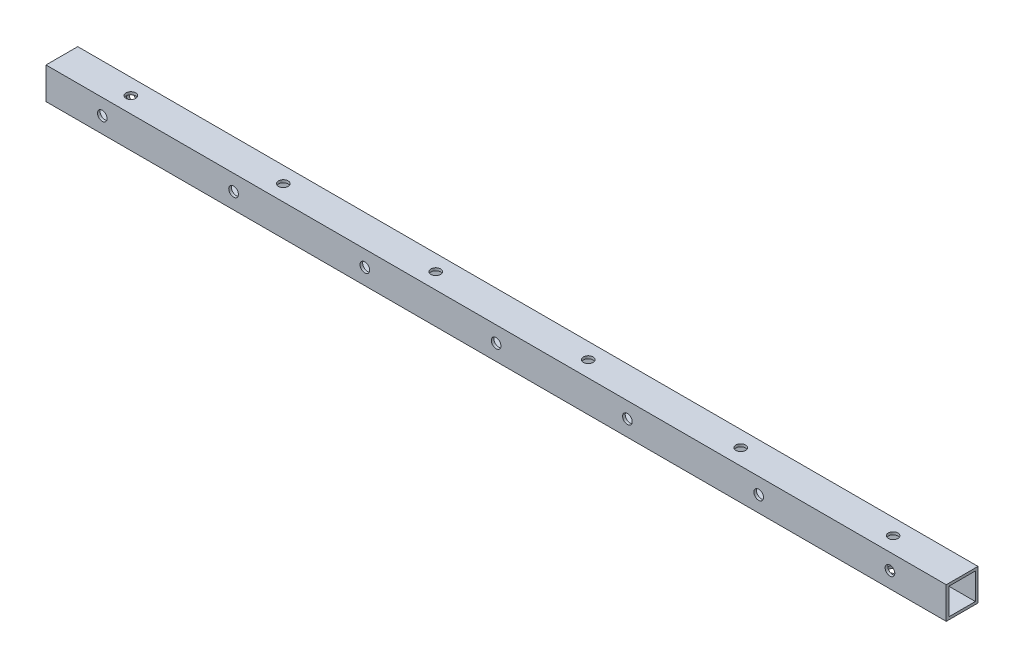
SolidWorks part; units mm, degrees
material "1060 Alloy"
ref_plane "Front Plane" through (0, 0, 0) normal (0, 0, 1) x (1, 0, 0)
ref_plane "Top Plane" through (0, 0, 0) normal (0, 1, 0) x (1, 0, 0)
ref_plane "Right Plane" through (0, 0, 0) normal (1, 0, 0) x (0, 0, -1)
sketch "Sketch1" plane through (0, 0, 0) normal (1, 0, 0) x (0, -1, 0)
  line L1 (-9.525, 9.525) -> (9.525, 9.525)
  line L2 (-9.525, 9.525) -> (-9.525, -9.525)
  line L3 (-9.525, -9.525) -> (9.525, -9.525)
  line L4 (9.525, 9.525) -> (9.525, -9.525)
  line L5 (-9.525, 9.525) -> (9.525, -9.525) construction
  line L6 (-9.525, -9.525) -> (9.525, 9.525) construction
  line L7 (-7.9375, 7.9375) -> (7.9375, 7.9375)
  line L8 (-7.9375, 7.9375) -> (-7.9375, -7.9375)
  line L9 (-7.9375, -7.9375) -> (7.9375, -7.9375)
  line L10 (7.9375, 7.9375) -> (7.9375, -7.9375)
  line L11 (-7.9375, 7.9375) -> (7.9375, -7.9375) construction
  line L12 (-7.9375, -7.9375) -> (7.9375, 7.9375) construction
  point P0 (0, 0)
  point P5 (0, 0)
  dimension "D2" = 19.05
  dimension "D1" = 15.875
extrude "Tube" add sketch "Sketch1" along normal blind 539.9532
sketch "Sketch2" plane through (0, 0, 9.525) normal (0, 0, 1) x (1, 0, 0)
  line L0 (506.1966, 0) -> (539.9532, 0) construction
  line L1 (539.9532, 9.525) -> (539.9532, -9.525) construction
  line L2 (539.9532, 0) -> (559.0032, 0) construction
  line L4 (559.0032, 0) -> (562.0766, 0) construction
  circle A2 centre (506.1966, 0) radius 2.8956
  dimension "D1" = 5.7912
  dimension "D2" = 19.05
  dimension "D3" = 3.0734
  dimension "D4" = 55.88
extrude "RearWallHoles" cut sketch "Sketch2" against normal through all
pattern_linear "LPattern1" count 7 spacing 78.74 along (-1, 0, 0) of "RearWallHoles"
sketch "Sketch3" plane through (0, 9.525, 0) normal (0, 1, 0) x (1, 0, 0)
  line L0 (0, 0) -> (-19.05, 0) construction
  line L1 (-19.05, 0) -> (-22.1234, 0) construction
  line L2 (0, 0) -> (41.3766, 0) construction
  circle A0 centre (41.3766, 0) radius 2.8956
  dimension "D1" = 5.7912
  dimension "D2" = 3.0734
  dimension "D3" = 19.05
  dimension "D4" = 63.5
extrude "RearTopHoleMaster" cut sketch "Sketch3" against normal through all
pattern_linear "LPattern2" count 6 spacing 91.44 along (1, 0, 0) of "RearTopHoleMaster"
equation "\"Height\"= 32in"
equation "\"Width\"= 23in"
equation "\"Depth\"= 20in"
equation "\"Plexi\"= .121in"
equation "\"Cutwidth\"= .016in"
equation "\"Earsize\"= 1in + \"Cutwidth\" /2"
equation "\"Slotsize\" = 1in - \"CutWidth\" / 2"
equation "\"InnerHeight\" = \"Height\" -2 * \"Plexi\""
equation "\"InnerWidth\" = \"Width\" - 2* \"Plexi\""
equation "\"RearHoleSpacing\" = (\"Width\" - 2*\"RearHolesBorder\") / (\"RearNumHoles\"-1)"
equation "\"D4@Sketch2\"=\"RearHolesBorder\""
equation "\"Boxsize\" = .75in"
equation "\"Boxinner\" = .625in"
equation "\"InnerDepth\" = \"Depth\" - 2*\"Plexi\""
equation "\"RearNumHoles\" = 7"
equation "\"RearHolesBorder\" = 2.2"
equation "\"SideVertNumHoles\" = 6"
equation "\"SideVertHolesBorder\" = \"CornerCube\"+\"FingerLength\"+.9"
equation "\"RivetDia\" = .228in"
equation "\"SlotDepth\" = \"Plexi\" + 0.75in + .005in"
equation "\"SideSlotWidth\"   = \"Plexi\"+.005in"
equation "\"SidePanelVertSpacing\" = (\"Height\"-2*(1.75-\"Plexi\")) / 5"
equation "\"BottomPanelSideHoleSpacing\" = (\"InnerDepth\"-2*(1.75-\"Plexi\")) / 4"
equation "\"D2@Sketch1\"=\"Boxsize\""
equation "\"D1@Sketch1\"=\"Boxinner\""
equation "\"CornerCube\" = 0.75in"
equation "\"RearBarLength\" = (\"InnerWidth\"-2*\"CornerCube\")"
equation "\"D1@Sketch2\"=\"RivetDia\""
equation "\"D2@Sketch2\"=\"CornerCube\""
equation "\"D3@Sketch2\"=\"Plexi\""
equation "\"D3@LPattern1\"=\"RearHoleSpacing\""
equation "\"D1@LPattern1\"=\"RearNumHoles\""
equation "\"D1@Tube\"=\"RearBarLength\""
equation "\"D1@Sketch3\"=\"RivetDia\""
equation "\"D2@Sketch3\"=\"Plexi\""
equation "\"D3@Sketch3\"=\"CornerCube\""
equation "\"RearTopNumHoles\" = 6"
equation "\"RearTopHolesBorder\" = 2.5"
equation "\"RearTopHolesSpacing\" = (\"Width\" - 2*\"RearTopHolesBorder\") / (\"RearTopNumHoles\"-1)"
equation "\"SideVertHoleSpacing\" = (\"InnerHeight\" - 2*\"SideVertHolesBorder\") / (\"SideVertNumHoles\"-1)"
equation "\"D4@Sketch3\"=\"RearTopHolesBorder\""
equation "\"D3@LPattern2\"=\"RearTopHolesSpacing\""
equation "\"D1@LPattern2\"=\"RearTopNumHoles\""
